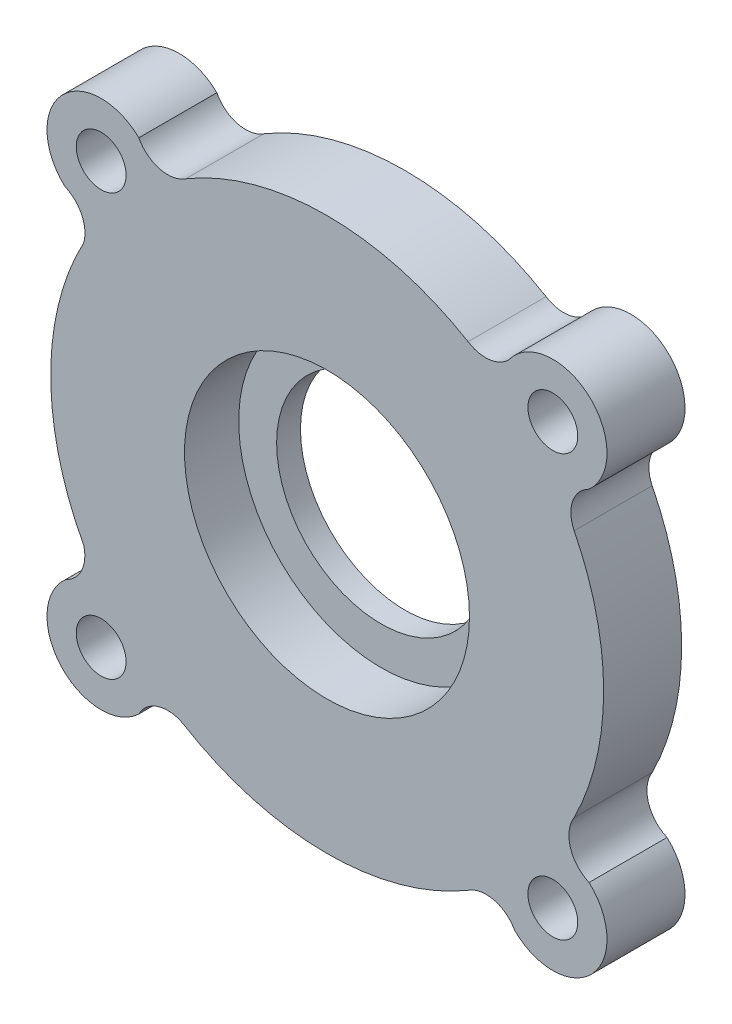
SolidWorks part; units mm, degrees
ref_plane "Спереди" through (0, 0, 0) normal (0, 0, 1) x (1, 0, 0)
ref_plane "Сверху" through (0, 0, 0) normal (0, 1, 0) x (1, 0, 0)
ref_plane "Справа" through (0, 0, 0) normal (1, 0, 0) x (0, 0, -1)
sketch "Эскиз1" plane through (0, 0, 0) normal (0, 0, 1) x (1, 0, 0)
  line L1 (20.8436, -19.437) -> (-20.8436, -19.437) construction
  line L2 (20.8436, -19.437) -> (20.8436, 19.437) construction
  line L3 (20.8436, 19.437) -> (-20.8436, 19.437) construction
  line L4 (-20.8436, -19.437) -> (-20.8436, 19.437) construction
  line L5 (20.8436, -19.437) -> (-20.8436, 19.437) construction
  line L6 (20.8436, 19.437) -> (-20.8436, -19.437) construction
  arc A1 (-22.7481, 11.5227) -> (-22.7481, -11.5227) centre (0, 0) ccw construction
  arc A2 (13.0814, 21.8889) -> (-13.0814, 21.8889) centre (0, 0) ccw construction
  arc A3 (22.7481, -11.5227) -> (23.7066, -15.3378) centre (25.4244, -12.8783) ccw construction
  arc A4 (-23.7066, -15.3378) -> (-22.7481, -11.5227) centre (-25.4244, -12.8783) ccw construction
  circle A25 centre (0, 0) radius 9.65
  circle A34 centre (-20.8436, -19.437) radius 2.3
  circle A35 centre (20.8436, -19.437) radius 2.3
  circle A36 centre (20.8436, 19.437) radius 2.3
  circle A37 centre (-20.8436, 19.437) radius 2.3
  arc A66 (17.3186, -22.983) -> (24.1865, -15.7188) centre (20.8436, -19.437) ccw
  arc A67 (22.8142, -11.2086) -> (24.1865, -15.7188) centre (25.4244, -12.8783) ccw
  arc A68 (22.8142, -11.2086) -> (22.8142, 11.7072) centre (0.0334, 0.2493) ccw
  arc A69 (24.1865, 15.7188) -> (22.8142, 11.7072) centre (25.5088, 13.0259) ccw
  arc A70 (24.1865, 15.7188) -> (16.8008, 22.3791) centre (20.8436, 19.437) ccw
  arc A71 (13.0191, 21.9261) -> (16.8008, 22.3791) centre (14.6343, 24.4542) ccw
  arc A72 (13.0191, 21.9261) -> (-13.0191, 21.9261) centre (0, 0) ccw
  arc A73 (-17.3677, 23.0311) -> (-13.0191, 21.9261) centre (-14.7028, 24.409) ccw
  arc A74 (-17.3677, 23.0311) -> (-24.1865, 15.7188) centre (-20.8436, 19.437) ccw
  arc A75 (-22.4566, 12.081) -> (-24.1865, 15.7188) centre (-25.3745, 12.9237) ccw
  arc A76 (-22.4566, 12.081) -> (-22.4569, -12.0806) centre (0, 0) ccw
  arc A77 (-24.1214, -15.6612) -> (-22.4569, -12.0806) centre (-25.4244, -12.8783) ccw
  arc A78 (-24.1214, -15.6612) -> (-17.3677, -23.0311) centre (-20.8436, -19.437) ccw
  arc A79 (-13.2509, -21.7868) -> (-17.3677, -23.0311) centre (-14.704, -24.4114) ccw
  arc A80 (-13.2509, -21.7868) -> (13.0191, -21.9261) centre (0, 0) ccw
  arc A81 (17.3186, -22.983) -> (13.0191, -21.9261) centre (14.6855, -24.4207) ccw
  point P1 (0, 0)
  point P6 (0, 0)
  point P10 (0, 0)
  point P13 (0, 0)
  point P16 (0, 0)
  dimension "D1" = 19.3
  dimension "D4" = 5
  dimension "D5" = 25.5
  dimension "D2" = 4.6
  dimension "D3" = 57
extrude "Бобышка-Вытянуть1" add sketch "Эскиз1" along normal blind 7.2
sketch "Эскиз3" plane through (0, 0, 7.2) normal (0, 0, 1) x (1, 0, 0)
  circle A0 centre (0, 0) radius 13.15
  dimension "D1" = 26.3
extrude "Вырез-Вытянуть2" cut sketch "Эскиз3" against normal blind 5
sketch "Эскиз4" plane through (0, 0, 0) normal (0, 0, -1) x (-1, 0, 0)
  circle A0 centre (0, 0) radius 18.8
  dimension "D1" = 37.6
extrude "Вырез-Вытянуть3" [suppressed] cut sketch "Эскиз4" against normal blind 0.2
